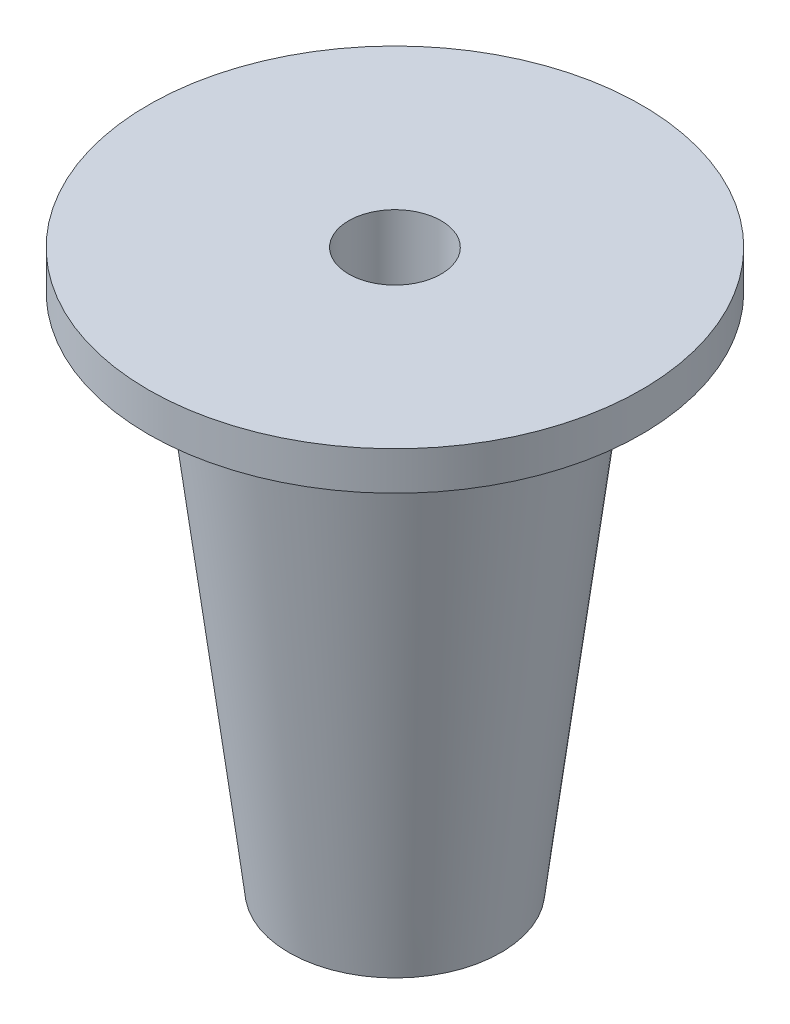
SolidWorks part; units mm, degrees
material "1060 Alloy"
ref_plane "Front Plane" through (0, 0, 0) normal (0, 0, 1) x (1, 0, 0)
ref_plane "Top Plane" through (0, 0, 0) normal (0, 1, 0) x (1, 0, 0)
ref_plane "Right Plane" through (0, 0, 0) normal (1, 0, 0) x (0, 0, -1)
sketch "Sketch2" plane through (0, 0, 0) normal (0, 0, 1) x (1, 0, 0)
  line L2 (22.0224, 80.3656) -> (32, 80.3656)
  line L3 (32, 80.3656) -> (32, 85.3656)
  line L4 (0, 13) -> (13.7509, 13)
  line L5 (13.7509, 13) -> (22.0224, 80.3656)
  line L6 (0, 13) -> (13.7509, 13)
  line L7 (13.7509, 13) -> (22.0224, 80.3656)
  line L8 (32, 85.3656) -> (0, 85.3656)
  line L9 (0, 0) -> (0, 113.2499) construction
  line L10 (0, 85.3656) -> (0, 13) construction
  line L11 (30, 0) -> (30, 80) construction
  line L14 (0, 13) -> (0, 85.3656)
  dimension "D2" = 5
  dimension "D3" = 2
  dimension "D1" = 3
revolve "Revolve1" add sketch "Sketch2" angle 360 about L10
sketch "Sketch3" plane through (0, 85.3656, 0) normal (0, 1, 0) x (1, 0, 0)
  circle A0 centre (0, 0) radius 6
  dimension "D1" = 12
extrude "Cut-Extrude1" cut sketch "Sketch3" against normal blind 20
